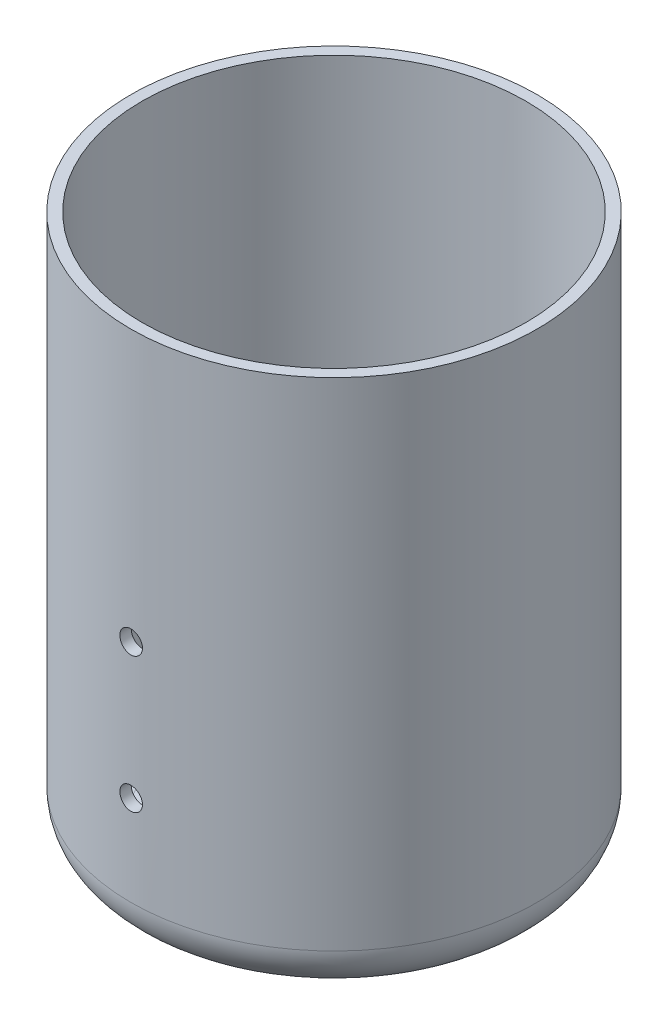
SolidWorks part; units mm, degrees
ref_plane "Front Plane" through (0, 0, 0) normal (0, 0, 1) x (1, 0, 0)
ref_plane "Top Plane" through (0, 0, 0) normal (0, 1, 0) x (1, 0, 0)
ref_plane "Right Plane" through (0, 0, 0) normal (1, 0, 0) x (0, 0, -1)
sketch "Sketch1" plane through (0, 0, 0) normal (1, 0, 0) x (0, 0, -1)
  line L0 (0, 51.8585) -> (0, -45.7575) construction
  line L1 (-42.5, 55) -> (-42.5, -52.5)
  line L2 (-32.5, -62.5) -> (0, -62.5)
  line L3 (-45, 55) -> (-45, -55)
  line L4 (-35, -65) -> (0, -65)
  line L5 (-45, 55) -> (-42.5, 55)
  line L6 (0, -62.5) -> (0, -65)
  line L7 (-45, 55) -> (-45, -65) construction
  line L8 (-45, -65) -> (0, -65) construction
  line L9 (-42.5, 55) -> (-42.5, -62.5) construction
  line L10 (-42.5, -62.5) -> (0, -62.5) construction
  arc A0 (-45, -55) -> (-35, -65) centre (-35, -55) ccw
  arc A1 (-42.5, -52.5) -> (-32.5, -62.5) centre (-32.5, -52.5) ccw
  point P9 (-45, 0)
  dimension "D4" = 10
  dimension "D1" = 2.5
  dimension "D2" = 85
  dimension "D3" = 120
revolve "Revolve1" add sketch "Sketch1" angle 360 about L0
sketch "Sketch2" plane through (0, -65, 0) normal (0, -1, 0) x (1, 0, 0)
  line L0 (0, 48.3799) -> (0, -50.1413) construction
  line L1 (-47.8928, 0) -> (56.3453, 0) construction
  circle A2 centre (0, 12.5) radius 6
  circle A3 centre (0, -12.5) radius 6
  dimension "D1" = 12
  dimension "D2" = 12.5
extrude "Cut-Extrude1" cut sketch "Sketch2" against normal through all both and the other way through all
sketch "Sketch4" plane through (0, 0, 0) normal (0, 0, 1) x (1, 0, 0)
  line L0 (-34.2474, -20) -> (25.5224, -20) construction
  line L1 (42.5, 55) -> (-42.5, 55) construction
  circle A0 centre (0, -5) radius 2.5
  circle A1 centre (0, -35) radius 2.5
  dimension "D1" = 5
  dimension "D2" = 30
  dimension "D3" = 75
extrude "Cut-Extrude2" cut sketch "Sketch4" along normal through all both and the other way through all
